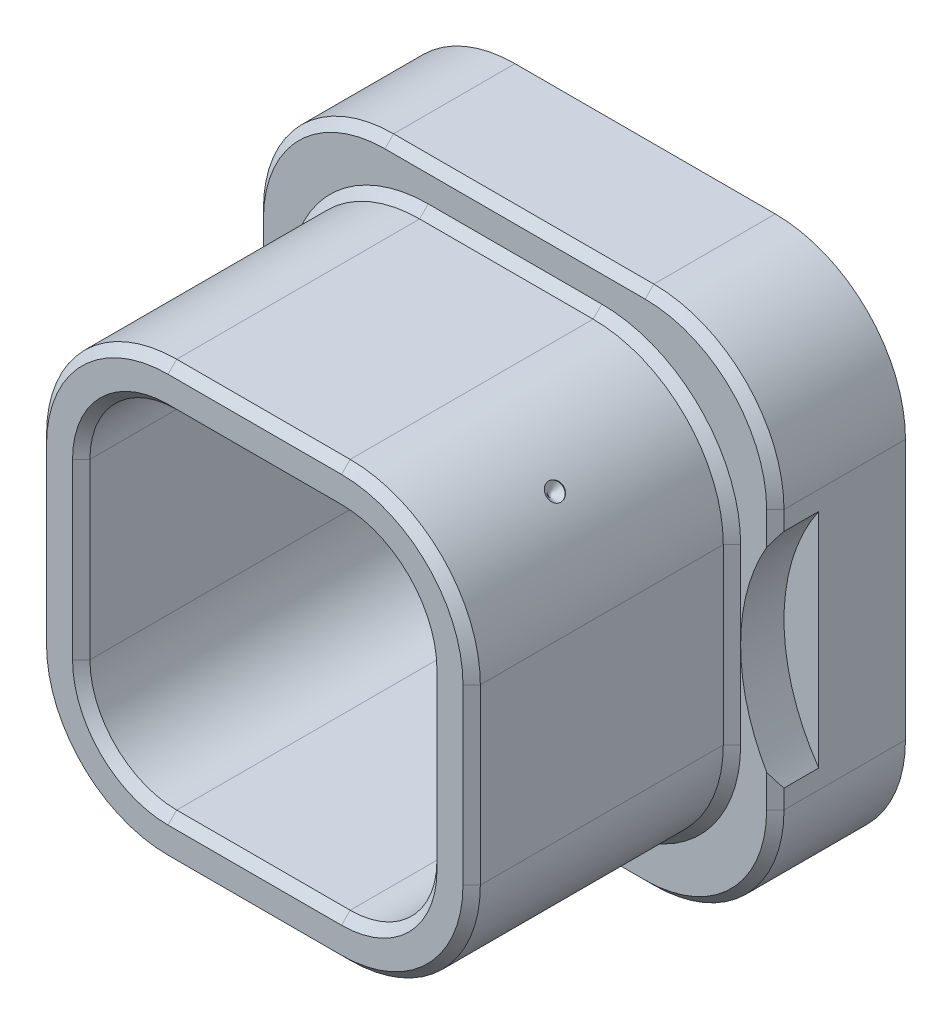
SolidWorks part; units mm, degrees
ref_plane "Ebene vorne" through (0, 0, 0) normal (0, 0, 1) x (1, 0, 0)
ref_plane "Ebene oben" through (0, 0, 0) normal (0, 1, 0) x (1, 0, 0)
ref_plane "Ebene rechts" through (0, 0, 0) normal (1, 0, 0) x (0, 0, -1)
sketch "Skizze1" plane through (0, 0, 0) normal (0, 0, 1) x (1, 0, 0)
  line L5 (-3, -3) -> (3, -3)
  line L6 (-3, -3) -> (-3, 3)
  line L7 (-3, 3) -> (3, 3)
  line L8 (3, -3) -> (3, 3)
  line L9 (-3, -3) -> (3, 3) construction
  line L10 (-3, 3) -> (3, -3) construction
  point P0 (0, 0)
  dimension "D1" = 6
  dimension "D2" = 6
extrude "Aufsatz-Linear austragen1" add sketch "Skizze1" against normal blind 1.5
sketch "Skizze2" plane through (0, 0, 0) normal (0, 0, -1) x (-1, 0, 0)
  line L0 (-2.5, 2.5) -> (2.5, 2.5)
  line L1 (-2.5, 2.5) -> (-2.5, -2.5)
  line L2 (-2.5, -2.5) -> (2.5, -2.5)
  line L3 (2.5, 2.5) -> (2.5, -2.5)
  line L4 (-2.5, 2.5) -> (2.5, -2.5) construction
  line L5 (-2.5, -2.5) -> (2.5, 2.5) construction
  line L6 (-1.9742, 1.9493) -> (2.0255, -2) construction
  line L7 (-1.9997, -1.9745) -> (2.0255, 2) construction
  point P0 (0, 0)
  point P5 (0, 0)
  point P10 (0, 0)
  dimension "D1" = 5
  dimension "D2" = 5
  dimension "D3" = 4
  dimension "D4" = 4
extrude "Aufsatz-Linear austragen2" add sketch "Skizze2" against normal blind 3
sketch "Skizze3" plane through (0, 0, 3) normal (0, 0, 1) x (1, 0, 0)
  line L0 (-2, 2) -> (2, 2)
  line L1 (-2, 2) -> (-2, -2)
  line L2 (-2, -2) -> (2, -2)
  line L3 (2, 2) -> (2, -2)
  line L4 (-2, 2) -> (2, -2) construction
  line L5 (-2, -2) -> (2, 2) construction
  point P0 (0, 0)
  point P5 (0, 0)
  dimension "D1" = 4
  dimension "D2" = 4
extrude "Schnitt-Linear austragen1" cut sketch "Skizze3" against normal blind 3.5
fillet "Verrundung1" radius 1 4 edges at (-2, -2, 1.25) (2, -2, 1.25) (2, 2, 1.25) (-2, 2, 1.25)
fillet "Verrundung2" radius 1.5 4 edges at (-2.5, -2.5, 1.5) (2.5, -2.5, 1.5) (2.5, 2.5, 1.5) (-2.5, 2.5, 1.5)
fillet "Verrundung3" radius 1.5 4 edges at (-3, -3, -0.75) (3, -3, -0.75) (3, 3, -0.75) (-3, 3, -0.75)
chamfer "Fase1" distance 0.1 angle 45 32 edges at (2.5607, -2.5607, 0) (3, 0, 0) (2.5607, 2.5607, 0) (0, 3, 0) (-2.5607, 2.5607, 0) (-3, 0, 0) (-2.5607, -2.5607, 0) (0, -3, 0) (2.0607, -2.0607, 3) (2.5, 0, 3) (2.0607, 2.0607, 3) (0, 2.5, 3) (-2.0607, 2.0607, 3) (-2.5, 0, 3) (-2.0607, -2.0607, 3) (0, -2.5, 3) (1.7071, 1.7071, 3) (0, 2, 3) (-1.7071, 1.7071, 3) (-2, 0, 3) (-1.7071, -1.7071, 3) (0, -2, 3) (1.7071, -1.7071, 3) (2, 0, 3) (2.0607, 2.0607, 0) (0, 2.5, 0) (-2.0607, 2.0607, 0) (-2.5, 0, 0) (-2.0607, -2.0607, 0) (0, -2.5, 0) (2.0607, -2.0607, 0) (2.5, 0, 0)
sketch "Skizze4" plane through (0, 0, 0) normal (0, 0, 1) x (1, 0, 0)
  line L0 (0, 0) -> (0, 1.8559) construction
  line L1 (0, 0) -> (2.5607, 2.5607) construction
  point P3 (0, 0)
  dimension "D1" = 45
ref_plane "Ebene1" through (2.0607, 2.0607, 0) normal (0.7071, 0.7071, 0) x (0.7071, -0.7071, 0)
hole_wizard "Ø0.2 (0.2) Durchmesser Bohrung5" positions "Skizze5" profile "Skizze6" hole size "Ø0.2" standard "DIN"
sketch "Skizze5" plane through (2.0607, 2.0607, 0) normal (0.7071, 0.7071, 0) x (0.7071, -0.7071, 0)
  line L0 (1.0607, -0.1) -> (-1.0607, -0.1) construction
  point P0 (0, -1.6)
  dimension "D1" = 1.5
sketch "Skizze6" plane through (2.0607, 2.0607, 1.6) normal (0, 0, 1) x (-0.7071, 0.7071, 0)
  line L0 (0, 0) -> (0, 0.11)
  line L1 (0, 0.11) -> (0.1, 0.01)
  line L2 (0.1, 0.01) -> (0.1, 0)
  line L5 (0.1, 0) -> (0, 0)
  line L10 (0, 0.11) -> (-0.1, 0.01) construction
  line L11 (0, -6.35) -> (0, 107.95) construction
  dimension "Bohrerdurchmesser" = 0.2
  dimension "Bohrungstiefe" = 0.01
  dimension "Spitzenwinkel" = 90
sketch "Skizze7" plane through (0, 0, 0) normal (0, 0, 1) x (1, 0, 0)
  line L0 (-2.6, -1) -> (-2.6, 1) construction
  line L3 (0, -2.475) -> (0, 2.475) construction
  circle A0 centre (-4.85, 0) radius 2.25
  circle A2 centre (4.85, 0) radius 2.25
  point P8 (0, 0)
  dimension "D1" = 4.5
extrude "Schnitt-Linear austragen2" cut sketch "Skizze7" against normal blind 0.5
